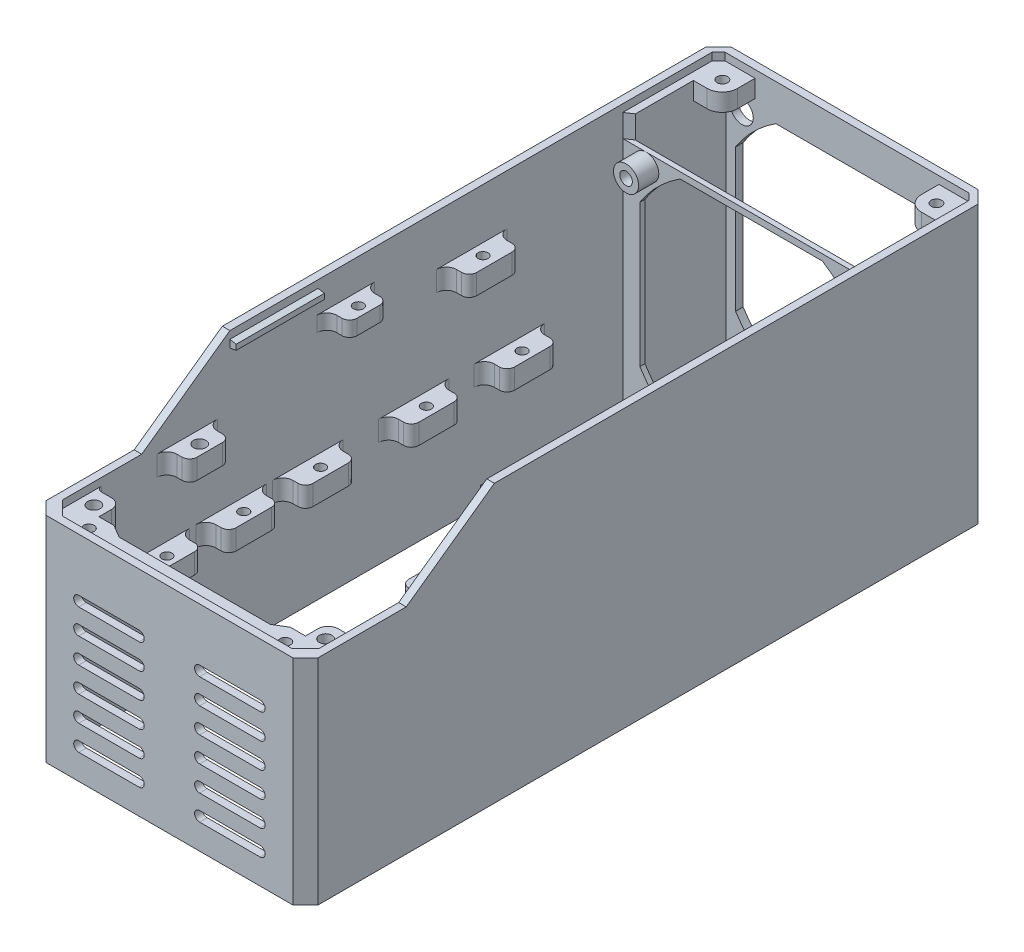
SolidWorks part; units mm, degrees
ref_plane "Alzado" through (0, 0, 0) normal (0, 0, 1) x (1, 0, 0)
ref_plane "Planta" through (0, 0, 0) normal (0, 1, 0) x (1, 0, 0)
ref_plane "Vista lateral" through (0, 0, 0) normal (1, 0, 0) x (0, 0, -1)
sketch "Croquis2" plane through (0, 0, 0) normal (0, 1, 0) x (1, 0, 0)
  line L0 (0, 0) -> (-146.5637, 0) construction
  line L1 (0, 0) -> (0, 180.9729) construction
  line L2 (49, 125) -> (-49, 125)
  line L3 (-49, 125) -> (-54, 120)
  line L4 (-54, 120) -> (-54, 0)
  line L5 (-51, 0) -> (-51, 84)
  line L6 (-51, 84) -> (51, 84)
  line L7 (48, 86) -> (-48, 86)
  line L8 (-48, 86) -> (-48, 122)
  line L9 (-48, 122) -> (48, 122)
  line L13 (49, 125) -> (54, 120)
  line L15 (48, 86) -> (48, 122)
  line L16 (54, 120) -> (54, 0)
  line L17 (51, 0) -> (51, 84)
  line L18 (-51, 0) -> (-51, -138.5)
  line L19 (-54, 0) -> (-54, -142)
  line L20 (-54, -142) -> (-49, -147)
  line L21 (-49, -147) -> (49, -147)
  line L22 (0, 0) -> (0, -150.9791) construction
  line L23 (-45.5, -144) -> (45.5, -144)
  line L24 (54, -142) -> (49, -147)
  line L25 (54, 0) -> (54, -142)
  line L26 (51, 0) -> (51, -138.5)
  line L27 (45.5, -144) -> (51, -138.5)
  line L28 (-45.5, -144) -> (-51, -138.5)
  point P15 (0, 116)
  point P23 (0, 125)
  point P24 (0, 122)
  point P26 (0, 122)
  point P27 (0, 84)
  point P28 (0, 86)
  point P33 (0, -144)
  point P36 (0, -147)
  dimension "D1" = 45
  dimension "D2" = 49
  dimension "D3" = 3
  dimension "D4" = 125
  dimension "D5" = 3
  dimension "D6" = 54
  dimension "D7" = 91
  dimension "D9" = 36
  dimension "D11" = 2
  dimension "D12" = 147
  dimension "D13" = 3
  dimension "D14" = 48
extrude "Saliente-Extruir1" add sketch "Croquis2" along normal blind 110
ref_plane "Plano1" through (0, 50, 0) normal (0, 1, 0) x (1, 0, 0)
sketch "Croquis3" plane through (0, 50, 0) normal (0, 1, 0) x (1, 0, 0)
  line L0 (-45, 49) -> (-47, 49)
  line L1 (-45, 29) -> (-47, 29)
  line L2 (51, 84) -> (-51, 84) construction
  line L3 (-51, 84) -> (-51, -138.5) construction
  line L8 (-51, 25) -> (-51, 53)
  line L9 (-42, 46) -> (-42, 32)
  line L10 (-51, 53) -> (-51, 74.9676)
  line L11 (-51, 25) -> (-51, 14.303)
  circle A0 centre (-46, 39) radius 2
  circle A1 centre (-46, 39) radius 3.5 construction
  arc A2 (-51, 25) -> (-47, 29) centre (-47, 25) cw
  arc A4 (-47, 49) -> (-51, 53) centre (-47, 53) cw
  arc A5 (-45, 49) -> (-42, 46) centre (-45, 46) cw
  arc A6 (-42, 32) -> (-45, 29) centre (-45, 32) cw
  point P25 (-42, 49)
  point P28 (-42, 29)
  point P31 (-42, 39)
  dimension "D4" = 4
  dimension "D5" = 7
  dimension "D6" = 4
  dimension "D7" = 9
  dimension "D9" = 4
  dimension "D12" = 3
  dimension "D2" = 45
  dimension "D3" = 20
extrude "Saliente-Extruir2" add sketch "Croquis3" against normal blind 8
sketch "Croquis11" plane through (0, 50, 0) normal (0, 1, 0) x (1, 0, 0)
  line L0 (-51, 84) -> (-51, -138.5) construction
  line L1 (-51, 84) -> (-51, -138.5)
  line L2 (-42, -48) -> (-42, -34)
  line L3 (-45, -31) -> (-47, -31)
  line L4 (-45, -51) -> (-47, -51)
  line L5 (-51, -27) -> (-51, -12.618)
  line L6 (-51, -55) -> (-51, -67.465)
  line L7 (-42, 46) -> (-42, 32) construction
  line L8 (-47, 29) -> (-47, 49)
  line L9 (-46, -51) -> (-46, -31) construction
  line L10 (-42, -41) -> (-51, -41) construction
  circle A0 centre (-46, -41) radius 2
  arc A1 (-42, -34) -> (-45, -31) centre (-45, -34) ccw
  arc A2 (-42, -48) -> (-45, -51) centre (-45, -48) cw
  arc A3 (-47, -51) -> (-51, -55) centre (-47, -55) ccw
  arc A4 (-47, -31) -> (-51, -27) centre (-47, -27) cw
  circle A5 centre (-46, 39) radius 2 construction
  circle A6 centre (-46, 39) radius 2
  arc A7 (-47, 29) -> (-51, 25) centre (-47, 25) ccw construction
  arc A8 (-47, 29) -> (-51, 25) centre (-47, 25) ccw
  arc A9 (-45, 29) -> (-42, 32) centre (-45, 32) ccw construction
  arc A10 (-45, 29) -> (-42, 32) centre (-45, 32) ccw
  point P16 (-51, -51)
  point P19 (-51, -27.9477)
  point P43 (-46, -31)
  dimension "D1" = 3
  dimension "D2" = 80
extrude "Saliente-Extruir7" add sketch "Croquis11" against normal up to surface (8 mm away) contours L3 A4 L1 A3 L4 A2 L2 A1 A0 up to face at (-46.3018, 42, -39)
pattern_linear "MatrizL1" count 2 spacing 38 along (0, 0, 1) of "Saliente-Extruir2"
pattern_linear "MatrizL2" count 3 spacing 30.5 along (0, 0, 1) of "Saliente-Extruir7"
mirror "Simetría1" about plane through (0, 0, 0) normal (1, 0, 0) of "MatrizL2", "MatrizL1", "Saliente-Extruir2", "Saliente-Extruir7"
sketch "Croquis4" plane through (0, 0, -84) normal (0, 0, 1) x (1, 0, 0)
  line L0 (51, 110) -> (-51, 110) construction
  line L1 (-28.2522, 95.5) -> (28.2522, 95.5)
  line L2 (44.25, 79.5022) -> (44.25, 22.9978)
  line L3 (28.2522, 7) -> (-28.2522, 7)
  line L4 (-44.25, 79.5022) -> (-44.25, 22.9978)
  line L5 (51, 0) -> (-51, 0) construction
  arc A0 (28.2522, 7) -> (44.25, 22.9978) centre (0, 51.25) ccw
  arc A1 (44.25, 79.5022) -> (28.2522, 95.5) centre (0, 51.25) ccw
  arc A2 (-28.2522, 95.5) -> (-44.25, 79.5022) centre (0, 51.25) ccw
  arc A3 (-44.25, 22.9978) -> (-28.2522, 7) centre (0, 51.25) ccw
  point P14 (0, 110)
  dimension "D1" = 105
  dimension "D2" = 88.5
  dimension "D3" = 44.25
  dimension "D4" = 7
extrude "Corte-Cooler" cut sketch "Croquis4" against normal blind 93
sketch "Croquis5" plane through (0, 0, -84) normal (0, 0, 1) x (1, 0, 0)
  line L0 (0, 51.25) -> (41.7193, 92.9693) construction
  line L1 (0, 51.25) -> (30.6107, 51.25) construction
  line L2 (0, 51.25) -> (41.7193, 92.9693) construction
  circle A0 centre (41.7193, 92.9693) radius 2.5
  arc A1 (44.25, 79.5022) -> (28.2522, 95.5) centre (0, 51.25) ccw construction
  arc A2 (44.25, 79.5022) -> (28.2522, 95.5) centre (0, 51.25) ccw
  circle A4 centre (41.7193, 9.5307) radius 2.5
  circle A5 centre (-41.7193, 9.5307) radius 2.5
  circle A6 centre (-41.7193, 92.9693) radius 2.5
  dimension "D1" = 5
  dimension "D3" = 45
  dimension "D5" = 59
  dimension "D4" = 4
extrude "Corte-CoolerAgujeros" cut sketch "Croquis5" against normal blind 57 contours A6 | A0 | A4 | A5
sketch "Croquis14" plane through (0, 0, -84) normal (0, 0, 1) x (1, 0, 0)
  circle A0 centre (41.7193, 92.9693) radius 5
  circle A1 centre (41.7193, 9.5307) radius 5
  circle A2 centre (-41.7193, 9.5307) radius 5
  circle A3 centre (-41.7193, 92.9693) radius 5
  circle M1 centre (-41.7193, 9.5307) radius 2.5
  circle M2 centre (41.7193, 9.5307) radius 2.5
  circle M3 centre (41.7193, 92.9693) radius 2.5
  circle M4 centre (-41.7193, 92.9693) radius 2.5
  dimension "D1" = 10
extrude "Extruir-InsertosCooler" add sketch "Croquis14" along normal blind 8 contours A0 M3 | A3 M4 | A2 M1 | A1 M2
sketch "Croquis20" plane through (0, 0, -125) normal (0, 0, -1) x (-1, 0, 0)
  circle A0 centre (41.7193, 92.9693) radius 4.5
  circle A1 centre (-41.7193, 92.9693) radius 4.5
  circle A2 centre (41.7193, 9.5307) radius 4.5
  circle A3 centre (-41.7193, 9.5307) radius 4.5
  dimension "D1" = 9
extrude "Cortar-Extruir6" cut sketch "Croquis20" against normal blind 10
sketch "Croquis15" plane through (0, 110, 0) normal (0, 1, 0) x (1, 0, 0)
  line L0 (-48, 86) -> (48, 86) construction
  line L1 (51, 84) -> (-51, 84) construction
  line L2 (-48, 86) -> (48, 86)
  line L3 (51, 84) -> (-51, 84)
  line L4 (-51, 84) -> (-48, 86)
  line L5 (51, 84) -> (48, 86)
extrude "Cortar-Extruir4" cut sketch "Croquis15" against normal blind 12
sketch "Croquis16" plane through (0, 110, 0) normal (0, 1, 0) x (1, 0, 0)
  line L0 (0, 122) -> (0, 97.5395) construction
  line L1 (48, 122) -> (-48, 122) construction
  line L2 (-42.5, 109) -> (-48, 109)
  line L3 (-48, 122) -> (-48, 86) construction
  line L4 (-36.5, 115) -> (-36.5, 122)
  line L5 (42.5, 109) -> (48, 109)
  line L6 (36.5, 115) -> (36.5, 122)
  line L7 (49, 125) -> (-49, 125) construction
  circle A0 centre (-42.5, 115) radius 2.1
  circle A1 centre (42.5, 115) radius 2.1
  arc A2 (-42.5, 109) -> (-36.5, 115) centre (-42.5, 115) ccw
  arc A3 (42.5, 109) -> (36.5, 115) centre (42.5, 115) cw
  line M5 (-48, 86) -> (-48, 122)
  line M6 (-48, 122) -> (48, 122)
  line M7 (48, 122) -> (48, 86)
  dimension "D1" = 4.2
  dimension "D2" = 10
  dimension "D3" = 85
  dimension "D4" = 6
extrude "Saliente-Extruir10" add sketch "Croquis16" against normal blind 7 from offset 3 contours L2 A2 L4 A0 M6 M5 | A3 L5 L6 A1 M7 M6 offset against normal yes
sketch "Croquis17" plane through (0, 110, 0) normal (0, 1, 0) x (1, 0, 0)
  line L0 (-36.5, 122) -> (-48.4645, 122)
  line L1 (-48.4645, 122) -> (-51, 119.4645)
  line L3 (-49, 125) -> (-54, 120) construction
  line L4 (0, 122) -> (0, 97.4214) construction
  line L5 (48, 122) -> (-48, 122) construction
  line L6 (-36.5, 122) -> (-36.5, 120)
  line L7 (-36.5, 115) -> (-36.5, 122) construction
  line L8 (-36.5, 120) -> (-39.0661, 120)
  line L9 (-39.0661, 120) -> (-47.4676, 111.5985)
  line L10 (-47.4676, 111.5985) -> (-47.4676, 109)
  line L11 (-42.5, 109) -> (-48, 109) construction
  line L21 (-51, 119.4645) -> (-51, 84)
  line L22 (-51, 84) -> (-47.4676, 84)
  line L23 (-47.4676, 84) -> (-47.4676, 109)
  line L33 (48, 122) -> (-48, 122) construction
  line L34 (47.4676, 84) -> (47.4676, 109)
  line L35 (51, 84) -> (47.4676, 84)
  line L36 (51, 119.4645) -> (51, 84)
  line L37 (47.4676, 111.5985) -> (47.4676, 109)
  line L38 (39.0661, 120) -> (47.4676, 111.5985)
  line L39 (36.5, 120) -> (39.0661, 120)
  line L40 (36.5, 122) -> (36.5, 120)
  line L41 (48.4645, 122) -> (51, 119.4645)
  line L42 (36.5, 122) -> (48.4645, 122)
  dimension "D1" = 2.5
  dimension "D3" = 2
extrude "Cortar-Extruir5" cut sketch "Croquis17" against normal blind 3
ref_plane "Plano3" through (0, 90, 0) normal (0, 1, 0) x (1, 0, 0)
sketch "Croquis9" plane through (0, 90, 0) normal (0, 1, 0) x (1, 0, 0)
  line L0 (-42, 46) -> (-42, 32) construction
  line L1 (-51, 25) -> (-51, 53) construction
  line L2 (-42, 24) -> (-51, 24) construction
  line L6 (42, 21) -> (42, 7)
  line L8 (-42, 17) -> (-42, 31)
  line L9 (-45, 34) -> (-47, 34)
  line L10 (-51, 38) -> (-51, 10)
  line L11 (-47, 14) -> (-45, 14)
  line L12 (0, 0) -> (0, -73.3957) construction
  line L13 (42, 61) -> (42, 47)
  line L14 (45, 64) -> (47, 64)
  line L15 (51, -138.5) -> (51, 119.4645) construction
  line L16 (51, 68) -> (51, 40)
  line L17 (45, 44) -> (47, 44)
  line L18 (45, 24) -> (47, 24)
  line L20 (42, 8) -> (42, -6) construction
  line L21 (46, 54) -> (46, 1) construction
  line L22 (51, 28) -> (51, 0)
  line L23 (45, 4) -> (47, 4)
  line L24 (46, 14) -> (46, -39) construction
  arc A0 (-42, 46) -> (-45, 49) centre (-45, 46) ccw construction
  circle A1 centre (-46.5, 24) radius 2
  arc A2 (-51, 53) -> (-47, 49) centre (-47, 53) ccw construction
  circle A3 centre (-46, 39) radius 2 construction
  arc A8 (-45, 14) -> (-42, 17) centre (-45, 17) ccw
  arc A9 (-42, 31) -> (-45, 34) centre (-45, 31) ccw
  arc A10 (-51, 38) -> (-47, 34) centre (-47, 38) ccw
  arc A11 (-47, 14) -> (-51, 10) centre (-47, 10) ccw
  arc A13 (47, 64) -> (51, 68) centre (47, 68) ccw
  arc A14 (51, 40) -> (47, 44) centre (47, 40) ccw
  arc A15 (42, 47) -> (45, 44) centre (45, 47) ccw
  arc A16 (42, 61) -> (45, 64) centre (45, 61) cw
  circle A17 centre (46, 54) radius 2
  arc A18 (47, 24) -> (51, 28) centre (47, 28) ccw
  arc A19 (51, 0) -> (47, 4) centre (47, 0) ccw
  arc A20 (42, 7) -> (45, 4) centre (45, 7) ccw
  arc A21 (42, 21) -> (45, 24) centre (45, 21) cw
  circle A22 centre (46, 14) radius 2
  circle A23 centre (46, 39) radius 2 construction
  point P13 (-42, 24)
  point P41 (51, -60)
  point P60 (51, 64)
  point P63 (51, -20)
  point P71 (42, 54)
  dimension "D3" = 40
  dimension "D1" = 2
  dimension "D4" = 10
  dimension "D2" = 15
extrude "Saliente-Extruir6" add sketch "Croquis9" against normal blind 8 contours A11 L11 A8 L8 A9 L9 A10 L10 A1 | A16 L13 A15 L17 A14 L16 A13 L14 A17 | A21 L6 A20 L23 A19 L22 A18 L18 A22
sketch "Croquis18" plane through (0, 90, 0) normal (0, 1, 0) x (1, 0, 0)
  line L0 (47, -18.5) -> (45, -18.5)
  line L1 (51, -138.5) -> (51, 119.4645) construction
  line L2 (42, -21.5) -> (42, -30.5)
  line L3 (45, -33.5) -> (47, -33.5)
  line L4 (51, -27) -> (51, -55) construction
  line L5 (51, -14.5) -> (51, -37.5)
  line L6 (51, -13) -> (51, 15) construction
  line L8 (42, -48) -> (42, -34) construction
  line L9 (0, 84) -> (0, -58.6208) construction
  line L10 (-51, 84) -> (51, 84) construction
  line L11 (-51, -14.5) -> (-51, -37.5)
  line L12 (-45, -33.5) -> (-47, -33.5)
  line L13 (-42, -21.5) -> (-42, -30.5)
  line L14 (-47, -18.5) -> (-45, -18.5)
  arc A0 (47, -33.5) -> (51, -37.5) centre (47, -37.5) cw
  arc A1 (51, -14.5) -> (47, -18.5) centre (47, -14.5) cw
  arc A2 (42, -30.5) -> (45, -33.5) centre (45, -30.5) ccw
  arc A3 (45, -18.5) -> (42, -21.5) centre (45, -21.5) ccw
  circle A4 centre (46, -26) radius 2
  arc A5 (42, -6) -> (45, -9) centre (45, -6) ccw construction
  arc A6 (51, -13) -> (47, -9) centre (47, -13) ccw construction
  circle A7 centre (-46, 39) radius 2 construction
  circle A8 centre (46, 1) radius 2 construction
  circle A9 centre (46, 1) radius 2
  circle A10 centre (-46, -26) radius 2
  arc A11 (-45, -18.5) -> (-42, -21.5) centre (-45, -21.5) cw
  arc A12 (-42, -30.5) -> (-45, -33.5) centre (-45, -30.5) cw
  arc A13 (-51, -14.5) -> (-47, -18.5) centre (-47, -14.5) ccw
  arc A14 (-47, -33.5) -> (-51, -37.5) centre (-47, -37.5) ccw
  point P14 (51, -28.3579)
  point P17 (51, -18.5)
  point P25 (42, -26)
  point P60 (-51, -18.5)
  point P61 (-51, -28.3579)
  dimension "D1" = 65
  dimension "D2" = 15
extrude "SoporteFrente" add sketch "Croquis18" against normal blind 6 from offset 8 contours L0 A3 L2 A2 L3 A0 L5 A1 A4 | A14 L12 A12 L13 A11 L14 A13 L11 A10
sketch "Croquis10" plane through (54, 0, 0) normal (1, 0, 0) x (0, 0, -1)
  line L0 (-147, 110) -> (-147, 85)
  line L1 (-147, 110) -> (-147, 0) construction
  line L2 (-147, 85) -> (-107, 85)
  line L3 (-107, 85) -> (-72, 110)
  line L6 (-142, 110) -> (120, 110) construction
  line L7 (-72, 110) -> (-147, 110)
  line L8 (-147, 110) -> (-147, 85)
  line L9 (-142, 0) -> (120, 0) construction
  dimension "D1" = 85
  dimension "D2" = 40
  dimension "D3" = 75
extrude "Corte-TapaBornera" cut sketch "Croquis10" against normal blind 123
ref_plane "Plano4" through (0, 82, 0) normal (0, 1, 0) x (1, 0, 0)
sketch "Croquis13" plane through (0, 82, 0) normal (0, 1, 0) x (1, 0, 0)
  line L0 (-41, -134) -> (-35, -134)
  line L1 (-51, -138.5) -> (-51, -107) construction
  line L3 (-51, -123) -> (-51, -102.8135)
  line L4 (-41, -134) -> (-41, -129)
  line L5 (-45, -125) -> (-49, -125)
  line L6 (-51, -138.5) -> (-51, -102.8135)
  line L8 (-51, -77) -> (-51, -107)
  line L9 (-42, -94) -> (-42, -84)
  line L10 (-45, -81) -> (-47, -81)
  line L11 (-45, -97) -> (-47, -97)
  line L12 (-51, -101) -> (-51, -102.8135)
  line L13 (45.5, -144) -> (-45.5, -144) construction
  line L14 (45.5, -144) -> (-45.5, -144)
  line L15 (-42, -109) -> (-42, -95) construction
  line L16 (-46, -97) -> (-46, -81) construction
  line L17 (-51, -101) -> (-51, -107)
  line L18 (0, -144) -> (0, -137)
  line L19 (-51, -138.5) -> (-45.5, -144)
  line L20 (-54, -142) -> (-54, -107) construction
  line L21 (-35, -134) -> (-30, -137)
  line L22 (-30, -137) -> (0, -137)
  arc A0 (-51, -123) -> (-49, -125) centre (-49, -123) ccw
  arc A2 (-41, -129) -> (-45, -125) centre (-45, -129) ccw
  circle A3 centre (-46, -131) radius 2.5
  circle A4 centre (-46, -89) radius 2.5
  arc A5 (-47, -81) -> (-51, -77) centre (-47, -77) cw
  arc A6 (-47, -97) -> (-51, -101) centre (-47, -101) ccw
  arc A7 (-42, -84) -> (-45, -81) centre (-45, -84) ccw
  arc A8 (-42, -94) -> (-45, -97) centre (-45, -94) cw
  circle A9 centre (-39, -140) radius 2.1
  circle A10 centre (-39, -140) radius 3 construction
  point P25 (-51, -95.245)
  dimension "D1" = 2
  dimension "D2" = 215
  dimension "D3" = 4
  dimension "D4" = 5
  dimension "D5" = 6
  dimension "D8" = 5
  dimension "D9" = 3
  dimension "D10" = 4
  dimension "D12" = 42
  dimension "D6" = 4.2
  dimension "D13" = 4
  dimension "D15" = 6
  dimension "D16" = 15
  dimension "D7" = 10
  dimension "D11" = 16
  dimension "D14" = 10
  dimension "D17" = 7
  dimension "D18" = 30
  dimension "D19" = 6
extrude "Saliente-Extruir8" add sketch "Croquis13" against normal blind 8
mirror "Simetría2" about plane through (0, 0, 0) normal (1, 0, 0) of "Saliente-Extruir8"
ref_plane "Plano5" through (0, 0, 37) normal (0, 0, 1) x (1, 0, 0)
sketch "Croquis19" plane through (0, 0, 37) normal (0, 0, 1) x (1, 0, 0)
  line L0 (51, 107) -> (48.5, 106.5592)
  line L1 (51, 110) -> (51, 85) construction
  line L2 (51, 110) -> (51, 85)
  line L3 (-51, 85) -> (-51, 110) construction
  line L4 (-51, 85) -> (-51, 110)
  line L5 (48.5, 106.5592) -> (48.5, 104.4408)
  line L6 (48.5, 104.4408) -> (51, 104)
  line L7 (51, 110) -> (54, 110) construction
  line L8 (0, 110) -> (0, 67.6533) construction
  line L9 (48.4645, 110) -> (-48.4645, 110) construction
  line L10 (-48.5, 104.4408) -> (-51, 104)
  line L11 (-48.5, 106.5592) -> (-48.5, 104.4408)
  line L12 (-51, 107) -> (-48.5, 106.5592)
  dimension "D1" = 80
  dimension "D2" = 80
  dimension "D3" = 2.5
  dimension "D4" = 3
  dimension "D5" = 3
extrude "Saliente-Canaleta" add sketch "Croquis19" along normal blind 35 contours L5 L6 L2 L0 | L12 L4 L10 L11
sketch "Croquis21" plane through (0, 0, 147) normal (0, 0, 1) x (1, 0, 0)
  line L0 (36, 62) -> (12, 62) construction
  line L1 (36, 60) -> (12, 60)
  line L2 (36, 64) -> (12, 64)
  line L3 (36, 52) -> (12, 52) construction
  line L4 (36, 50) -> (12, 50)
  line L5 (36, 54) -> (12, 54)
  line L6 (36, 42) -> (12, 42) construction
  line L7 (36, 40) -> (12, 40)
  line L8 (36, 44) -> (12, 44)
  line L9 (36, 32) -> (12, 32) construction
  line L10 (36, 30) -> (12, 30)
  line L11 (36, 34) -> (12, 34)
  line L12 (36, 22) -> (12, 22) construction
  line L13 (36, 20) -> (12, 20)
  line L14 (36, 24) -> (12, 24)
  line L15 (36, 12) -> (12, 12) construction
  line L16 (36, 10) -> (12, 10)
  line L17 (36, 14) -> (12, 14)
  line L18 (-12, 52) -> (-36, 52) construction
  line L19 (-12, 50) -> (-36, 50)
  line L20 (-12, 54) -> (-36, 54)
  line L21 (-12, 42) -> (-36, 42) construction
  line L22 (-12, 40) -> (-36, 40)
  line L23 (-12, 44) -> (-36, 44)
  line L24 (-12, 32) -> (-36, 32) construction
  line L25 (-12, 30) -> (-36, 30)
  line L26 (-12, 34) -> (-36, 34)
  line L27 (-12, 22) -> (-36, 22) construction
  line L28 (-12, 20) -> (-36, 20)
  line L29 (-12, 24) -> (-36, 24)
  line L30 (-12, 12) -> (-36, 12) construction
  line L31 (-12, 10) -> (-36, 10)
  line L32 (-12, 14) -> (-36, 14)
  line L33 (-12, 62) -> (-36, 62) construction
  line L34 (-12, 60) -> (-36, 60)
  line L35 (-12, 64) -> (-36, 64)
  line L36 (0, 74) -> (0, 0) construction
  line L37 (24, 62) -> (-24, 12) construction
  line L40 (45.5, 74) -> (-45.5, 74)
  line L41 (45.5, 0) -> (45.5, 74)
  line L42 (-45.5, 0) -> (45.5, 0)
  line L43 (-45.5, 74) -> (-45.5, 0)
  line L44 (45.5, 74) -> (-45.5, 74) construction
  line L45 (45.5, 0) -> (45.5, 74) construction
  line L46 (-45.5, 0) -> (45.5, 0) construction
  line L47 (-45.5, 74) -> (-45.5, 0) construction
  arc A0 (36, 60) -> (36, 64) centre (36, 62) ccw
  arc A1 (12, 64) -> (12, 60) centre (12, 62) ccw
  arc A2 (36, 50) -> (36, 54) centre (36, 52) ccw
  arc A3 (12, 54) -> (12, 50) centre (12, 52) ccw
  arc A4 (36, 40) -> (36, 44) centre (36, 42) ccw
  arc A5 (12, 44) -> (12, 40) centre (12, 42) ccw
  arc A6 (36, 30) -> (36, 34) centre (36, 32) ccw
  arc A7 (12, 34) -> (12, 30) centre (12, 32) ccw
  arc A8 (36, 20) -> (36, 24) centre (36, 22) ccw
  arc A9 (12, 24) -> (12, 20) centre (12, 22) ccw
  arc A10 (36, 10) -> (36, 14) centre (36, 12) ccw
  arc A11 (12, 14) -> (12, 10) centre (12, 12) ccw
  arc A12 (-12, 50) -> (-12, 54) centre (-12, 52) ccw
  arc A13 (-36, 54) -> (-36, 50) centre (-36, 52) ccw
  arc A14 (-12, 40) -> (-12, 44) centre (-12, 42) ccw
  arc A15 (-36, 44) -> (-36, 40) centre (-36, 42) ccw
  arc A16 (-12, 30) -> (-12, 34) centre (-12, 32) ccw
  arc A17 (-36, 34) -> (-36, 30) centre (-36, 32) ccw
  arc A18 (-12, 20) -> (-12, 24) centre (-12, 22) ccw
  arc A19 (-36, 24) -> (-36, 20) centre (-36, 22) ccw
  arc A20 (-12, 10) -> (-12, 14) centre (-12, 12) ccw
  arc A21 (-36, 14) -> (-36, 10) centre (-36, 12) ccw
  arc A22 (-12, 60) -> (-12, 64) centre (-12, 62) ccw
  arc A23 (-36, 64) -> (-36, 60) centre (-36, 62) ccw
  point P2 (24, 62)
  point P12 (24, 52)
  point P19 (24, 42)
  point P26 (24, 32)
  point P33 (24, 22)
  point P40 (24, 12)
  point P47 (-24, 52)
  point P54 (-24, 42)
  point P61 (-24, 32)
  point P68 (-24, 22)
  point P75 (-24, 12)
  point P82 (-24, 62)
  point P92 (0, 37)
  point P93 (0, 37)
  point P94 (26.1709, 9.2246)
  point P95 (0, 0)
  point P96 (20.7332, 12)
  dimension "D2" = 2
  dimension "D1" = 24
  dimension "D6" = 10
  dimension "D7" = 12
  dimension "D5" = 0
  dimension "D3" = 6
  dimension "D4" = 2
extrude "Cortar-Extruir7" cut sketch "Croquis21" against normal blind 10
